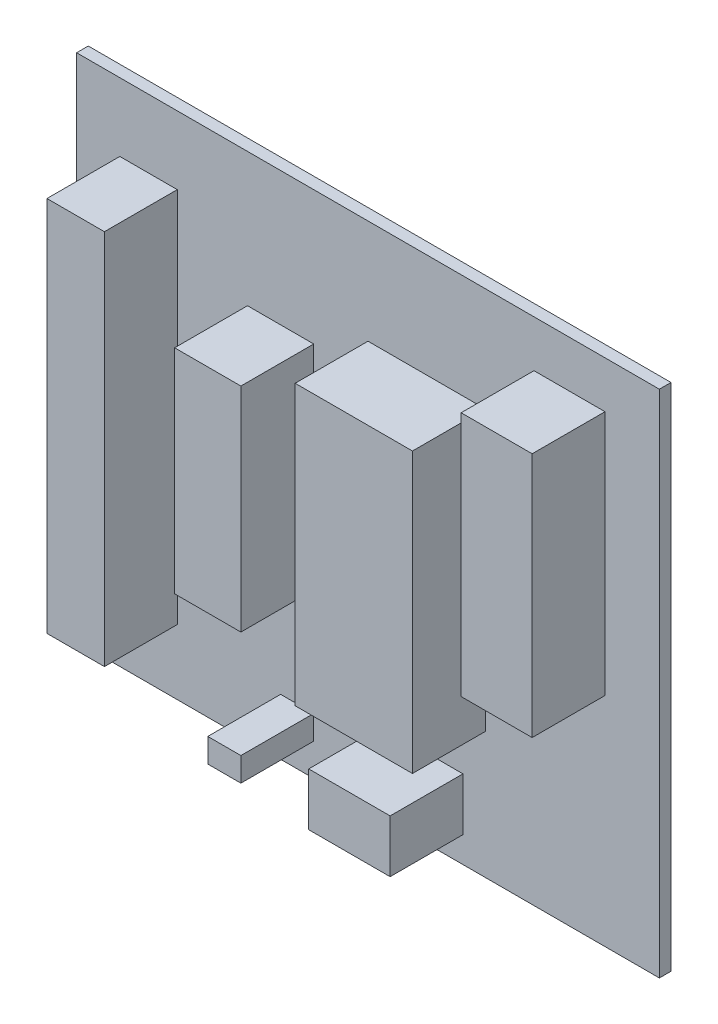
SolidWorks part; units mm, degrees
ref_plane "Top Plane" through (0, 0, 0) normal (0, 0, 1) x (1, 0, 0)
ref_plane "Right Plane" through (0, 0, 0) normal (0, 1, 0) x (1, 0, 0)
ref_plane "Front Plane" through (0, 0, 0) normal (1, 0, 0) x (0, 0, -1)
sketch "Sketch1" plane through (0, 0, 0) normal (0, 0, 1) x (1, 0, 0)
  line L0 (-40, 35) -> (40, -35) construction
  line L1 (-40, 35) -> (40, 35)
  line L2 (-40, 35) -> (-40, -35)
  line L3 (-40, -35) -> (40, -35)
  line L4 (40, 35) -> (40, -35)
  dimension "D1" = 80
  dimension "D2" = 70
extrude "Boss-Extrude1" add sketch "Sketch1" along normal mid plane 1.6
sketch "Sketch2" plane through (0, 0, 0.8) normal (0, 0, 1) x (1, 0, 0)
  line L1 (-16.5417, -12.598) -> (-7.4493, -12.598)
  line L2 (-16.5417, -12.598) -> (-16.5417, 16.6513)
  line L3 (-16.5417, 16.6513) -> (-7.4493, 16.6513)
  line L4 (-7.4493, -12.598) -> (-7.4493, 16.6513)
  line L5 (0, -17.6372) -> (16.1035, -17.6372)
  line L6 (0, -17.6372) -> (0, 20.7045)
  line L7 (0, 20.7045) -> (16.1035, 20.7045)
  line L8 (16.1035, -17.6372) -> (16.1035, 20.7045)
  line L9 (-34.0694, -26.0724) -> (-26.1819, -26.0724)
  line L10 (-34.0694, -26.0724) -> (-34.0694, 25.6342)
  line L11 (-34.0694, 25.6342) -> (-26.1819, 25.6342)
  line L12 (-26.1819, -26.0724) -> (-26.1819, 25.6342)
  line L13 (22.7859, -5.1487) -> (32.5357, -5.1487)
  line L14 (22.7859, -5.1487) -> (22.7859, 28.592)
  line L15 (22.7859, 28.592) -> (32.5357, 28.592)
  line L16 (32.5357, -5.1487) -> (32.5357, 28.592)
  line L17 (-11.9955, -30.5638) -> (-7.4493, -30.5638)
  line L18 (-11.9955, -30.5638) -> (-11.9955, -27.2774)
  line L19 (-11.9955, -27.2774) -> (-7.4493, -27.2774)
  line L20 (-7.4493, -30.5638) -> (-7.4493, -27.2774)
  line L21 (1.8623, -31.4402) -> (13.0362, -31.4402)
  line L22 (1.8623, -31.4402) -> (1.8623, -24.2101)
  line L23 (1.8623, -24.2101) -> (13.0362, -24.2101)
  line L24 (13.0362, -31.4402) -> (13.0362, -24.2101)
extrude "Boss-Extrude2" add sketch "Sketch2" along normal blind 10
